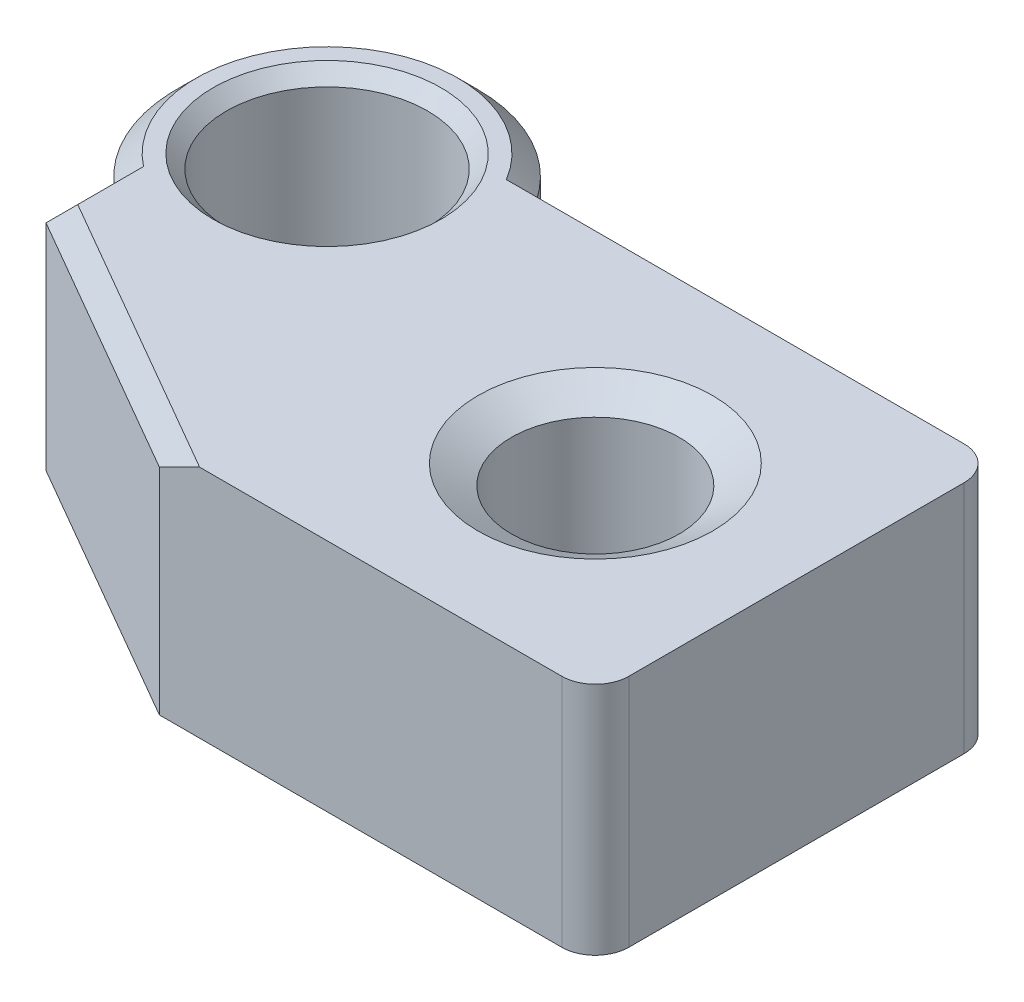
SolidWorks part; units mm, degrees
ref_plane "Front Plane" through (0, 0, 0) normal (0, 0, 1) x (1, 0, 0)
ref_plane "Top Plane" through (0, 0, 0) normal (0, 1, 0) x (1, 0, 0)
ref_plane "Right Plane" through (0, 0, 0) normal (1, 0, 0) x (0, 0, -1)
sketch "Sketch1" plane through (0, 0, 0) normal (0, 1, 0) x (1, 0, 0)
  line L0 (-40, -16.906) -> (0, -40)
  line L1 (-4.8444, 20) -> (65, 20)
  line L2 (-40, -6.7705) -> (-40, -16.906)
  line L3 (0, -40) -> (65, -40)
  line L4 (65, 20) -> (65, -40)
  line L5 (0, 0) -> (0, -40) construction
  arc A0 (-4.8444, 20) -> (-40, -6.7705) centre (-25, 10) ccw
  point P2 (-40, -11.8382)
  dimension "D5" = 45
  dimension "D1" = 10
  dimension "D2" = 60
  dimension "D3" = 40
  dimension "D4" = 90
  dimension "D6" = 150
  dimension "D7" = 40
  dimension "D8" = 105
extrude "Boss-Extrude1" add sketch "Sketch1" along normal blind 35 contours A0 L2 L0 L3 L4 L1
sketch "Sketch2" plane through (0, 0, 0) normal (0, 1, 0) x (1, 0, 0)
  circle A0 centre (35, -10) radius 12.5
  circle A1 centre (-25, 10) radius 15
  dimension "D3" = 25
  dimension "D4" = 30
  dimension "D1" = 35
  dimension "D2" = 10
extrude "Cut-Extrude3" cut sketch "Sketch2" against normal through all and the other way through all contours A0
chamfer "Chamfer1" distance 3 angle 45 3 edges at (-38.6312, 35, -27.9008) (-40, 35, 11.8382) (-20, 35, 28.453)
chamfer "Chamfer2" distance 2 angle 45 2 edges at (-25, 0, 5) (-25, 35, 5)
chamfer "Chamfer3" distance 5 angle 30 2 edges at (35, 0, 22.5) (35, 35, 22.5)
fillet "Fillet1" radius 5 3 edges at (65, 17.5, 40) (65, 17.5, -20) (-4.8444, 16, -20)
